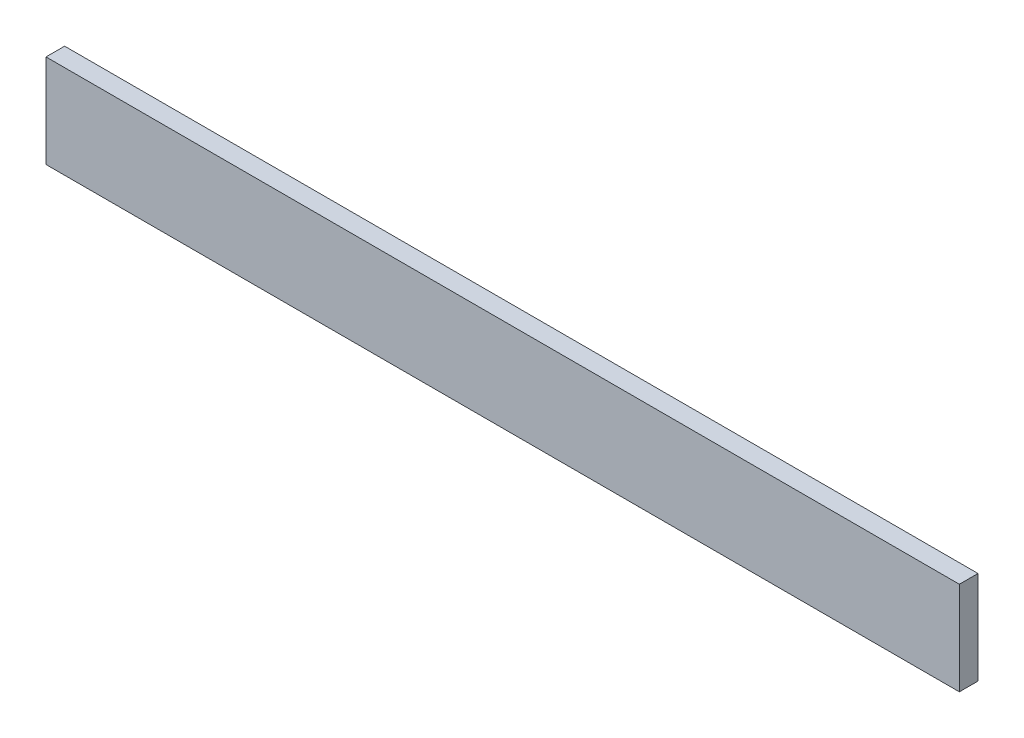
SolidWorks part; units mm, degrees
ref_plane "Ebene vorne" through (0, 0, 0) normal (0, 0, 1) x (1, 0, 0)
ref_plane "Ebene oben" through (0, 0, 0) normal (0, 1, 0) x (1, 0, 0)
ref_plane "Ebene rechts" through (0, 0, 0) normal (1, 0, 0) x (0, 0, -1)
sketch "Skizze1" plane through (0, 0, 0) normal (0, 0, 1) x (1, 0, 0)
  line L1 (-73.5, -7.5) -> (73.5, -7.5)
  line L2 (-73.5, -7.5) -> (-73.5, 7.5)
  line L3 (-73.5, 7.5) -> (73.5, 7.5)
  line L4 (73.5, -7.5) -> (73.5, 7.5)
  line L5 (-73.5, -7.5) -> (73.5, 7.5) construction
  line L6 (-73.5, 7.5) -> (73.5, -7.5) construction
  point P0 (0, 0)
  dimension "D1" = 15
  dimension "D2" = 147
extrude "Aufsatz-Linear austragen1" add sketch "Skizze1" along normal blind 3
